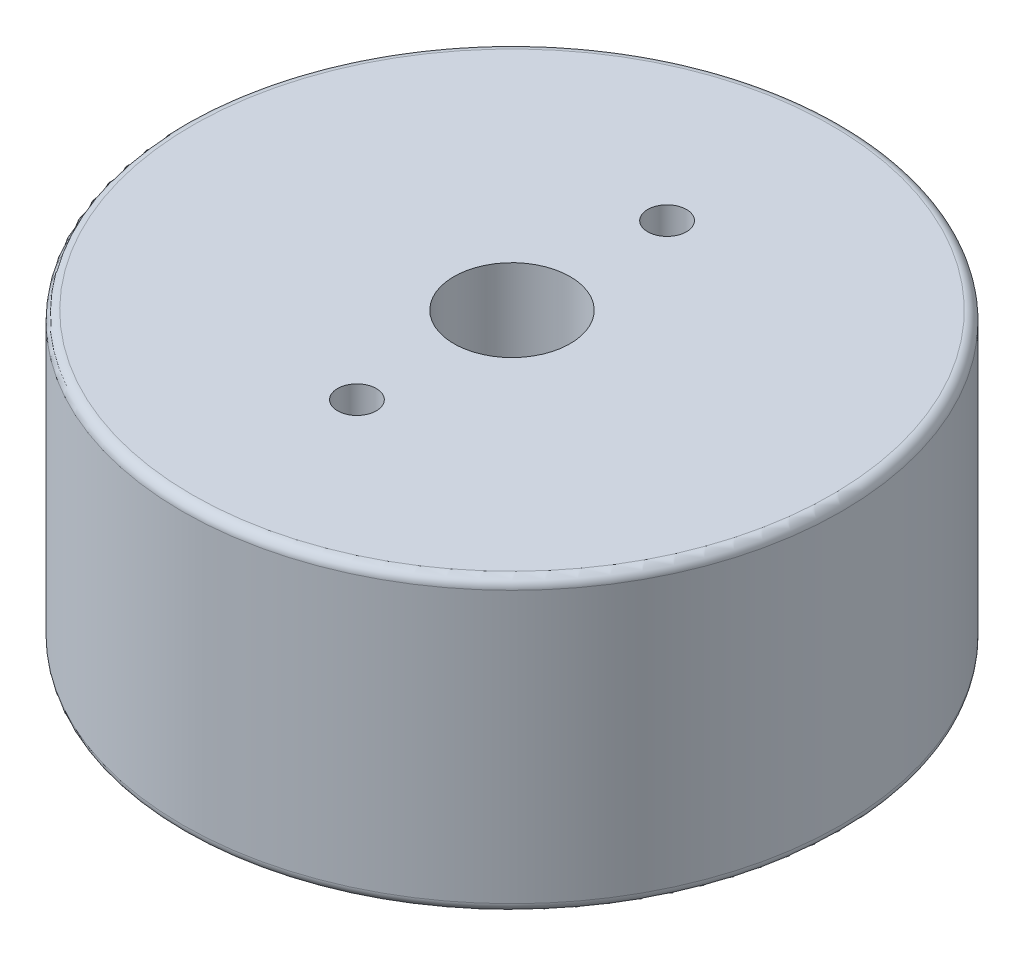
SolidWorks part; units mm, degrees
ref_plane "前视基准面" through (0, 0, 0) normal (0, 0, 1) x (1, 0, 0)
ref_plane "上视基准面" through (0, 0, 0) normal (0, 1, 0) x (1, 0, 0)
ref_plane "右视基准面" through (0, 0, 0) normal (1, 0, 0) x (0, 0, -1)
other "Configuration Table"
sketch "草图1" plane through (0, 0, 0) normal (0, 1, 0) x (1, 0, 0)
  circle A0 centre (0, 0) radius 17
  dimension "D1" = 34
extrude "凸台-拉伸1" add sketch "草图1" along normal blind 15
sketch "草图2" plane through (0, 15, 0) normal (0, 1, 0) x (1, 0, 0)
  line L0 (0, 8) -> (0, -8) construction
  circle A0 centre (0, 8) radius 1
  circle A1 centre (0, -8) radius 1
  dimension "D3" = 2
  dimension "D4" = 2
  dimension "D1" = 16
  dimension "D2" = 8
extrude "切除-拉伸1" cut sketch "草图2" against normal blind 10
sketch "草图4" plane through (0, 0, 0) normal (0, -1, 0) x (1, 0, 0)
  circle A0 centre (0, 0) radius 8 construction
  circle A1 centre (0, 8) radius 1.5
  circle A2 centre (8, 0) radius 1.5
  circle A3 centre (0, -8) radius 1.5
  circle A4 centre (-8, 0) radius 1.5
  point P14 (0, 0)
  dimension "D1" = 16
  dimension "D2" = 3
  dimension "D3" = 4
extrude "切除-拉伸3" cut sketch "草图4" against normal blind 2
sketch "草图5" plane through (0, 0, 0) normal (0, -1, 0) x (1, 0, 0)
  circle A0 centre (0, 0) radius 3
  dimension "D1" = 6
extrude "切除-拉伸4" cut sketch "草图5" against normal up to next
fillet "圆角1" radius 0.5 2 edges at (0, 0, 17) (0, 15, 17)
